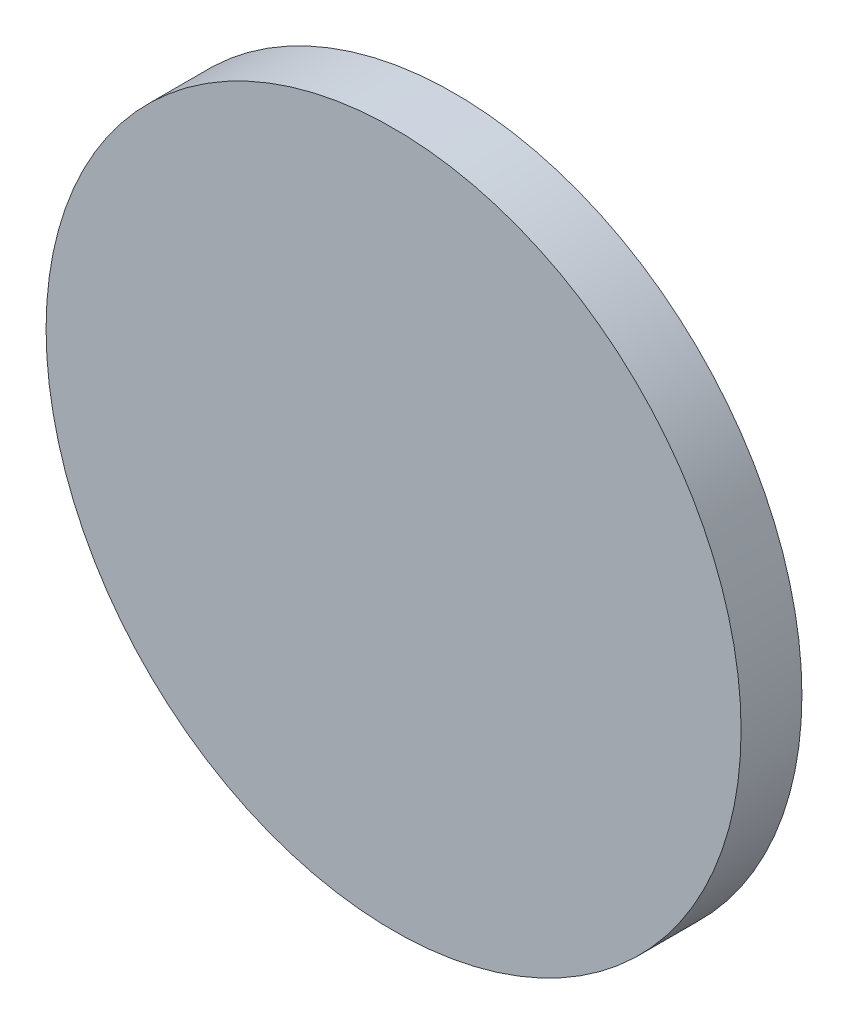
SolidWorks part; units mm, degrees
ref_plane "Front Plane" through (0, 0, 0) normal (0, 0, 1) x (1, 0, 0)
ref_plane "Top Plane" through (0, 0, 0) normal (0, 1, 0) x (1, 0, 0)
ref_plane "Right Plane" through (0, 0, 0) normal (1, 0, 0) x (0, 0, -1)
sketch "Sketch1" plane through (0, 0, 0) normal (0, 0, 1) x (1, 0, 0)
  circle A0 centre (0, 0) radius 57.1163
extrude "Boss-Extrude1" add sketch "Sketch1" along normal blind 10
